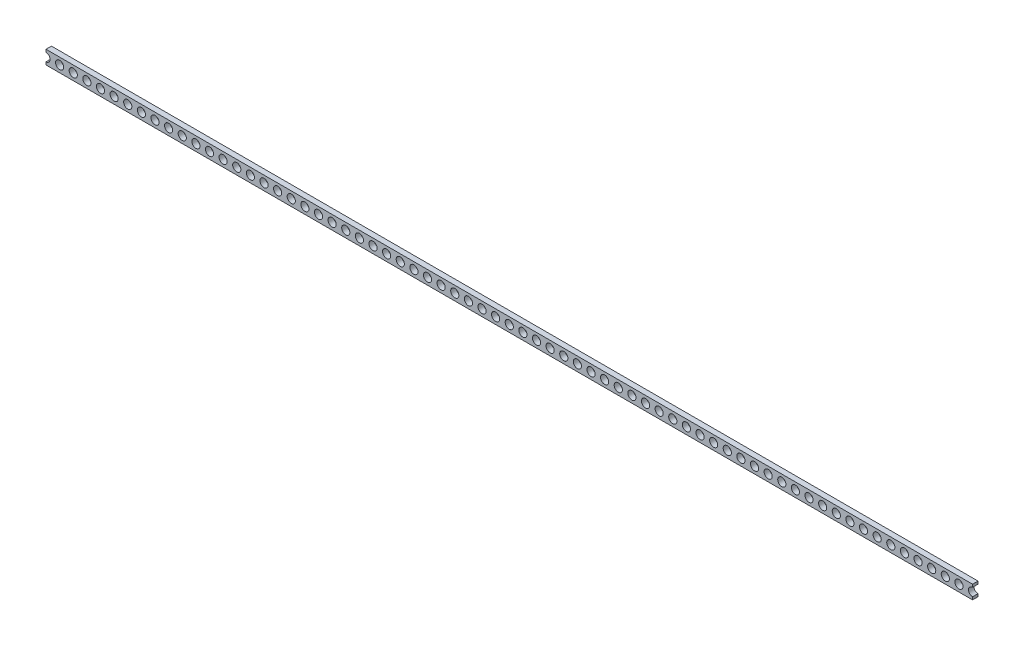
SolidWorks part; units mm, degrees
ref_plane "前视基准面" through (0, 0, 0) normal (0, 0, 1) x (1, 0, 0)
ref_plane "上视基准面" through (0, 0, 0) normal (0, 1, 0) x (1, 0, 0)
ref_plane "右视基准面" through (0, 0, 0) normal (1, 0, 0) x (0, 0, -1)
sketch "草图1" plane through (0, 0, 0) normal (0, 0, 1) x (1, 0, 0)
  line L1 (0, 0) -> (340, 0)
  line L2 (0, 0) -> (0, -5)
  line L3 (0, -5) -> (340, -5)
  line L4 (340, 0) -> (340, -5)
  dimension "D1" = 5
  dimension "D2" = 340
extrude "凸台-拉伸1" add sketch "草图1" along normal blind 2
sketch "草图2" plane through (0, 0, 2) normal (0, 0, 1) x (1, 0, 0)
  line L0 (340, 0) -> (0, 0) construction
  line L1 (170, 0) -> (170, -5) construction
  line L2 (0, -5) -> (340, -5) construction
  circle A0 centre (170, -2.5) radius 1.5
  point P2 (0, 0)
  point P9 (0, 0)
  point P10 (0, 0)
  dimension "D1" = 3
extrude "切除-拉伸1" cut sketch "草图2" against normal through all
pattern_linear "阵列(线性)1" count 35 spacing 5 along (1, 0, 0) of "切除-拉伸1"
pattern_linear "阵列(线性)2" count 35 spacing 5 along (-1, 0, 0) of "切除-拉伸1"
